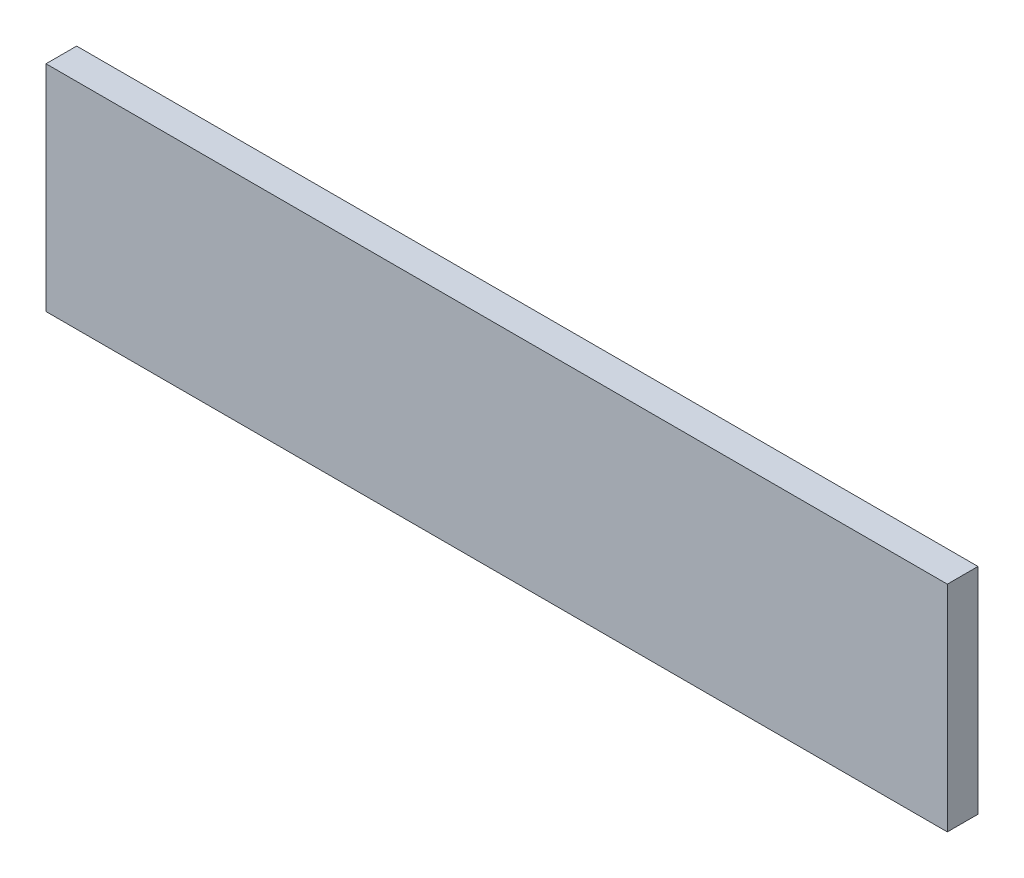
SolidWorks part; units mm, degrees
material "Plain Carbon Steel"
ref_plane "Front Plane" through (0, 0, 0) normal (0, 0, 1) x (1, 0, 0)
ref_plane "Top Plane" through (0, 0, 0) normal (0, 1, 0) x (1, 0, 0)
ref_plane "Right Plane" through (0, 0, 0) normal (1, 0, 0) x (0, 0, -1)
sketch "Sketch1" plane through (0, 0, 0) normal (0, 0, 1) x (1, 0, 0)
  line L0 (-47, -7) -> (-47, 63) construction
  line L1 (-47, 63) -> (247, 63)
  line L2 (-47, 63) -> (-47, -7)
  line L3 (-47, -7) -> (247, -7)
  line L4 (247, 63) -> (247, -7)
  line L5 (-47, 63) -> (-10, 63) construction
  line L6 (247, 63) -> (247, -7) construction
  line L7 (247, -7) -> (-47, -7) construction
extrude "Boss-Extrude1" add sketch "Sketch1" along normal blind 10
